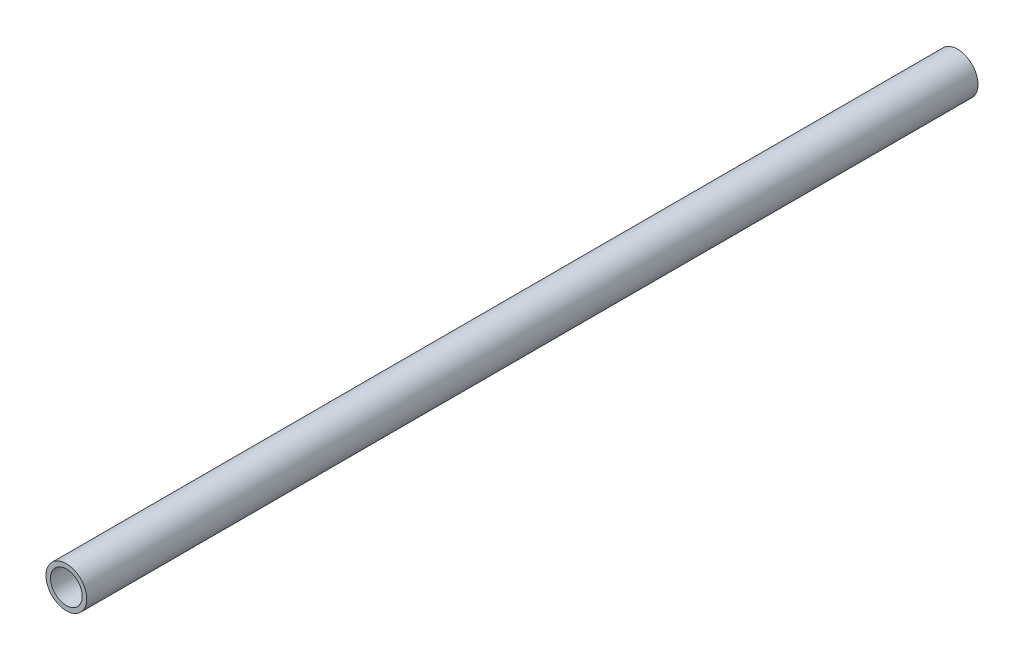
SolidWorks part; units mm, degrees
ref_plane "Front Plane" through (0, 0, 0) normal (0, 0, 1) x (1, 0, 0)
ref_plane "Top Plane" through (0, 0, 0) normal (0, 1, 0) x (1, 0, 0)
ref_plane "Right Plane" through (0, 0, 0) normal (1, 0, 0) x (0, 0, -1)
sketch "Sketch1" plane through (0, 0, 0) normal (0, 0, 1) x (1, 0, 0)
  circle A0 centre (0, 0) radius 9
  circle A1 centre (0, 0) radius 7
  dimension "D1" = 14
  dimension "D2" = 18
extrude "Boss-Extrude1" add sketch "Sketch1" along normal blind 393.26
